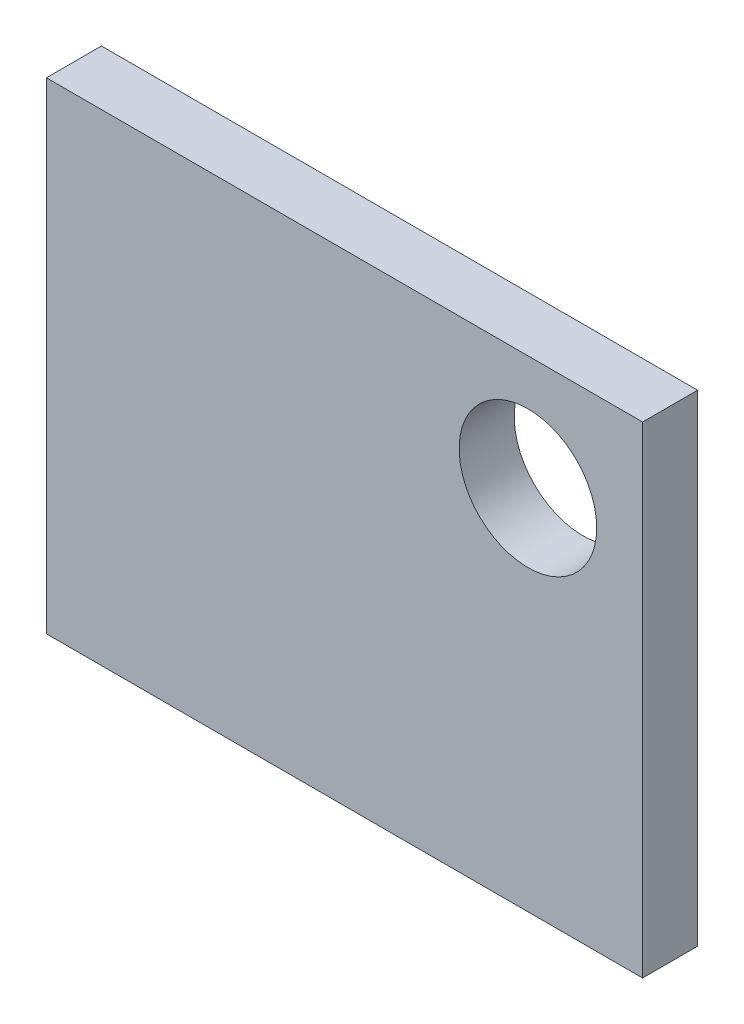
SolidWorks part; units mm, degrees
ref_plane "Спереди" through (0, 0, 0) normal (0, 0, 1) x (1, 0, 0)
ref_plane "Сверху" through (0, 0, 0) normal (0, 1, 0) x (1, 0, 0)
ref_plane "Справа" through (0, 0, 0) normal (1, 0, 0) x (0, 0, -1)
sketch "Skizze1" plane through (0, 0, 0) normal (0, 0, 1) x (1, 0, 0)
  line L1 (-5, 5) -> (8, 5)
  line L2 (-5, 5) -> (-5, -5.5)
  line L3 (-5, -5.5) -> (8, -5.5)
  line L4 (8, 5) -> (8, -5.5)
  dimension "D1" = 13
  dimension "D2" = 10.5
  dimension "D3" = 5
  dimension "D4" = 5
extrude "Aufsatz-Linear austragen1" add sketch "Skizze1" along normal blind 1.2
sketch "Skizze2" plane through (0, 0, 1.2) normal (0, 0, 1) x (1, 0, 0)
  line L0 (-5, 5) -> (-5, -5.5) construction
  line L1 (-5, -5.5) -> (8, -5.5) construction
  circle A0 centre (5.5, 2.5) radius 1.5
  dimension "D1" = 10.5
  dimension "D2" = 8
  dimension "D3" = 3
extrude "Schnitt-Linear austragen1" cut sketch "Skizze2" against normal blind 1.2
